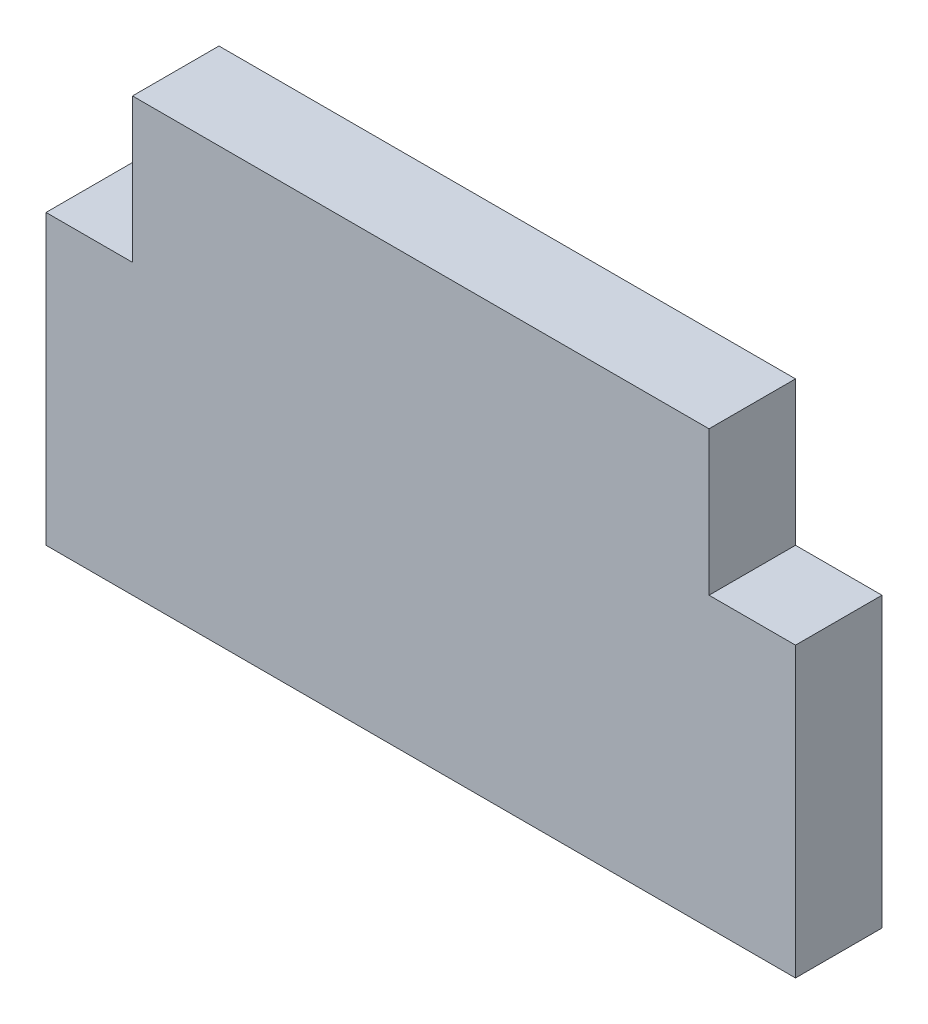
SolidWorks part; units mm, degrees
ref_plane "前视基准面" through (0, 0, 0) normal (0, 0, 1) x (1, 0, 0)
ref_plane "上视基准面" through (0, 0, 0) normal (0, 1, 0) x (1, 0, 0)
ref_plane "右视基准面" through (0, 0, 0) normal (1, 0, 0) x (0, 0, -1)
other "Configuration Table"
sketch "草图1" plane through (0, 0, 0) normal (0, 0, 1) x (1, 0, 0)
  line L0 (0, 6.5152) -> (0, -14.8485) construction
  line L1 (-10, 7.5) -> (10, 7.5)
  line L2 (-10, 7.5) -> (-10, -7.5)
  line L3 (-10, -7.5) -> (10, -7.5)
  line L4 (10, 7.5) -> (10, -7.5)
  line L5 (-10, 7.5) -> (10, -7.5) construction
  line L6 (-10, -7.5) -> (10, 7.5) construction
  line L7 (10, -7.5) -> (13, -7.5)
  line L8 (10, -7.5) -> (10, 2.5)
  line L9 (10, 2.5) -> (13, 2.5)
  line L10 (13, -7.5) -> (13, 2.5)
  line L11 (-10, 2.5) -> (-13, 2.5)
  line L12 (-13, -7.5) -> (-13, 2.5)
  line L13 (-10, -7.5) -> (-13, -7.5)
  line L14 (-10, -7.5) -> (-10, 2.5)
  point P0 (0, 0)
  dimension "D1" = 15
  dimension "D2" = 20
  dimension "D3" = 3
  dimension "D4" = 10
extrude "凸台-拉伸1" add sketch "草图1" along normal blind 3 contours L4 L1 L2 L3 | L7 L10 L9 L4 | L13 L2 L11 L12
